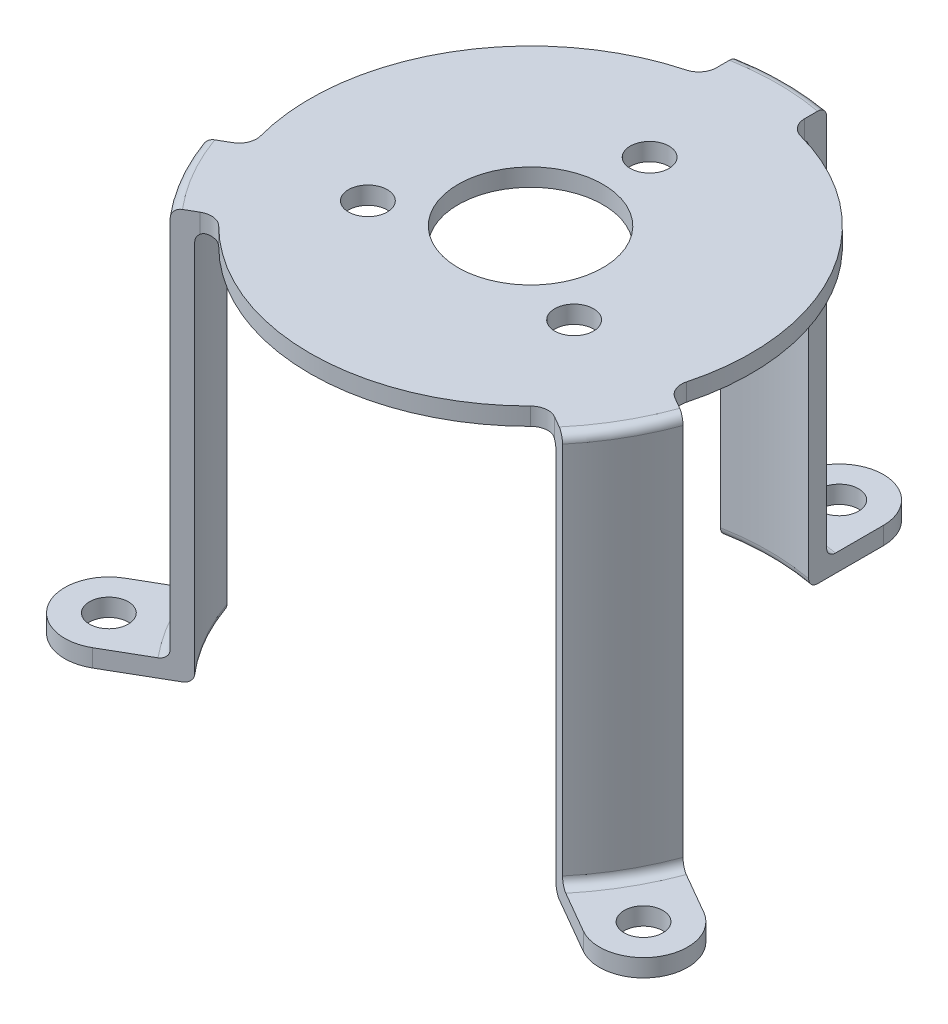
SolidWorks part; units mm, degrees
material "Liga 6061"
ref_plane "Plano frontal" through (0, 0, 0) normal (0, 0, 1) x (1, 0, 0)
ref_plane "Plano superior" through (0, 0, 0) normal (0, 1, 0) x (1, 0, 0)
ref_plane "Plano direito" through (0, 0, 0) normal (1, 0, 0) x (0, 0, -1)
sketch "Esboço1" plane through (0, 0, 0) normal (0, 1, 0) x (1, 0, 0)
  line L0 (0, 0) -> (0, -35.0841) construction
  line L1 (-2.5, 14.2829) -> (-2.5, 12.2474)
  line L2 (2.5, 14.2829) -> (2.5, 12.2474)
  line L3 (13.6193, -4.9764) -> (11.8566, -3.9587)
  line L4 (11.1193, -9.3065) -> (9.3566, -8.2888)
  line L5 (-11.1193, -9.3065) -> (-9.3566, -8.2888)
  line L6 (-13.6193, -4.9764) -> (-11.8566, -3.9587)
  circle A0 centre (0, 0) radius 4.1
  circle A1 centre (0, 0) radius 6.75 construction
  arc A2 (-9.3566, -8.2888) -> (9.3566, -8.2888) centre (0, 0) ccw
  arc A3 (-13.6193, -4.9764) -> (-11.1193, -9.3065) centre (0, 0) ccw
  circle A4 centre (0, 6.75) radius 1.1
  circle A5 centre (5.8457, -3.375) radius 1.1
  circle A6 centre (-5.8457, -3.375) radius 1.1
  arc A7 (11.1193, -9.3065) -> (13.6193, -4.9764) centre (0, 0) ccw
  arc A8 (11.8566, -3.9587) -> (2.5, 12.2474) centre (0, 0) ccw
  arc A9 (2.5, 14.2829) -> (-2.5, 14.2829) centre (0, 0) ccw
  arc A10 (-2.5, 12.2474) -> (-11.8566, -3.9587) centre (0, 0) ccw
  point P17 (0, 0)
  point P29 (0, 0)
  dimension "D1" = 3
  dimension "D2" = 8.2
  dimension "D3" = 2.2
  dimension "D4" = 13.5
  dimension "D7" = 2
  dimension "D8" = 12.5
  dimension "D6" = 5
  dimension "D5" = 3
extrude "Ressalto-extrusão1" add sketch "Esboço1" along normal blind 1
sketch "Esboço2" plane through (0, 0, 0) normal (0, -1, 0) x (1, 0, 0)
  line L0 (-11.1193, 9.3065) -> (-9.3566, 8.2888) construction
  line L1 (-11.8566, 3.9587) -> (-13.6193, 4.9764) construction
  line L2 (-2.5, -14.2829) -> (-2.5, -12.2474) construction
  line L3 (2.5, -12.2474) -> (2.5, -14.2829) construction
  line L4 (13.6193, 4.9764) -> (11.8566, 3.9587) construction
  line L5 (9.3566, 8.2888) -> (11.1193, 9.3065) construction
  line L6 (-11.1193, 9.3065) -> (-10.2391, 8.7983)
  line L7 (-12.7391, 4.4682) -> (-13.6193, 4.9764)
  line L8 (-2.5, -14.2829) -> (-2.5, -13.2665)
  line L9 (2.5, -13.2665) -> (2.5, -14.2829)
  line L10 (13.6193, 4.9764) -> (12.7391, 4.4682)
  line L11 (10.2391, 8.7983) -> (11.1193, 9.3065)
  arc A0 (-11.1193, 9.3065) -> (-13.6193, 4.9764) centre (0, 0) ccw construction
  arc A1 (13.6193, 4.9764) -> (11.1193, 9.3065) centre (0, 0) ccw construction
  arc A2 (-2.5, -14.2829) -> (2.5, -14.2829) centre (0, 0) ccw construction
  arc A3 (-11.1193, 9.3065) -> (-13.6193, 4.9764) centre (0, 0) ccw
  arc A4 (13.6193, 4.9764) -> (11.1193, 9.3065) centre (0, 0) ccw
  arc A5 (-2.5, -14.2829) -> (2.5, -14.2829) centre (0, 0) ccw
  arc A6 (-10.2391, 8.7983) -> (-12.7391, 4.4682) centre (0, 0) ccw
  arc A7 (12.7391, 4.4682) -> (10.2391, 8.7983) centre (0, 0) ccw
  arc A8 (-2.5, -13.2665) -> (2.5, -13.2665) centre (0, 0) ccw
  arc A9 (-10.3525, 8.6647) -> (-12.6801, 4.6332) centre (0, 0) ccw construction
  arc A10 (12.6801, 4.6332) -> (10.3525, 8.6647) centre (0, 0) ccw construction
  arc A11 (-2.3276, -13.2978) -> (2.3276, -13.2978) centre (0, 0) ccw construction
  dimension "D1" = 1
extrude "Ressalto-extrusão2" add sketch "Esboço2" along normal blind 22.2
sketch "Esboço3" plane through (0, -22.2, 0) normal (0, -1, 0) x (1, 0, 0)
  line L0 (2.5, -14.2829) -> (2.5, -17.5)
  line L1 (-2.5, -14.2829) -> (-2.5, -17.5)
  line L2 (-11.1193, 9.3065) -> (-13.9054, 10.9151)
  line L3 (-13.6193, 4.9764) -> (-16.4054, 6.5849)
  line L4 (13.6193, 4.9764) -> (16.4054, 6.5849)
  line L5 (11.1193, 9.3065) -> (13.9054, 10.9151)
  arc A0 (-2.5, -14.2829) -> (2.5, -14.2829) centre (0, 0) ccw construction
  arc A1 (-2.5, -14.2829) -> (2.5, -14.2829) centre (0, 0) ccw
  circle A2 centre (0, -17.5) radius 1.1
  arc A3 (-2.5, -17.5) -> (2.5, -17.5) centre (0, -17.5) ccw
  arc A4 (-11.1193, 9.3065) -> (-13.6193, 4.9764) centre (0, 0) ccw
  circle A5 centre (-15.1554, 8.75) radius 1.1
  arc A6 (-13.9054, 10.9151) -> (-16.4054, 6.5849) centre (-15.1554, 8.75) ccw
  arc A7 (13.6193, 4.9764) -> (11.1193, 9.3065) centre (0, 0) ccw
  circle A8 centre (15.1554, 8.75) radius 1.1
  arc A9 (16.4054, 6.5849) -> (13.9054, 10.9151) centre (15.1554, 8.75) ccw
  point P21 (0, 0)
  dimension "D2" = 17.5
  dimension "D3" = 2.2
  dimension "D1" = 3
extrude "Ressalto-extrusão3" add sketch "Esboço3" against normal blind 1
fillet "Filete1" radius 1 6 edges at (11.8566, 0.5, 3.9587) (2.5, 0.5, -12.2474) (-2.5, 0.5, -12.2474) (-11.8566, 0.5, 3.9587) (9.3566, 0.5, 8.2888) (-9.3566, 0.5, 8.2888)
fillet "Filete2" radius 0.5 3 edges at (-12.5574, 1, 7.25) (0, 1, -14.5) (12.5574, 1, 7.25)
fillet "Filete3" radius 0.5 3 edges at (0, 0, -13.5) (11.6913, 0, 6.75)
fillet "Filete4" radius 0.5 3 edges at (-12.5574, -21.2, 7.25) (0, -21.2, -14.5) (12.5574, -21.2, 7.25)
fillet "Filete5" radius 0.5 3 edges at (0, -22.2, -13.5) (-11.6913, -22.2, 6.75) (11.6913, -22.2, 6.75)
